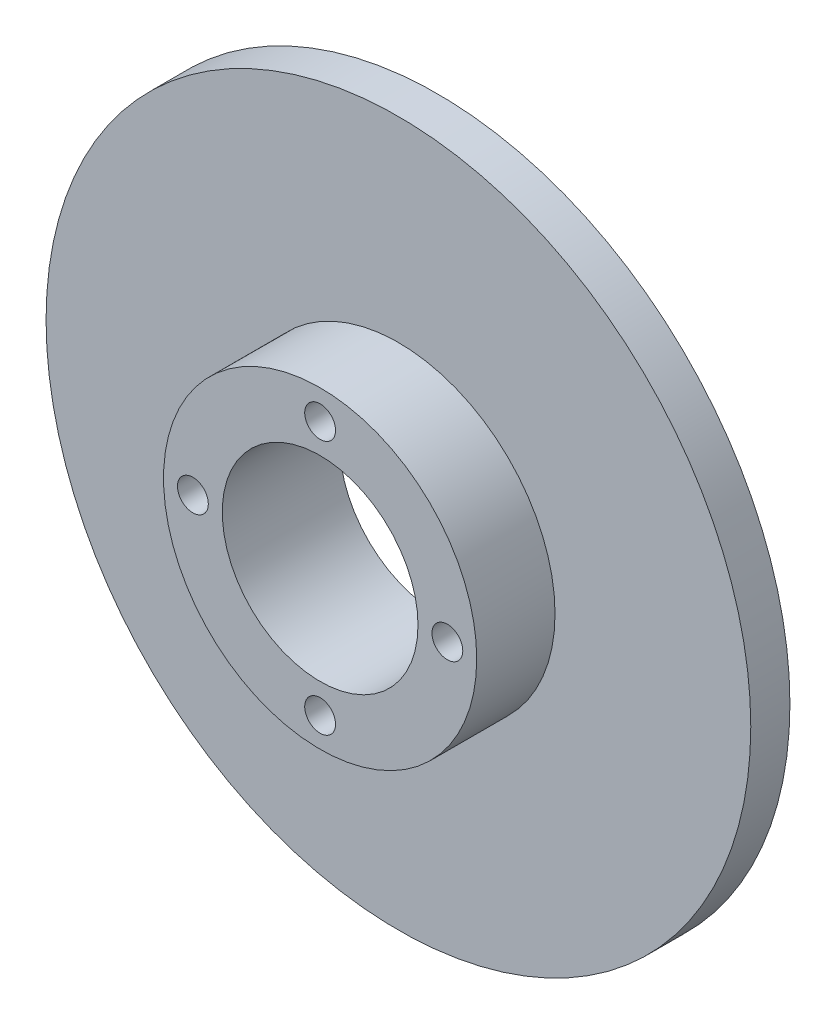
SolidWorks part; units mm, degrees
material "Stainless Steel (ferritic)"
ref_plane "Front Plane" through (0, 0, 0) normal (0, 0, 1) x (1, 0, 0)
ref_plane "Top Plane" through (0, 0, 0) normal (0, 1, 0) x (1, 0, 0)
ref_plane "Right Plane" through (0, 0, 0) normal (1, 0, 0) x (0, 0, -1)
sketch "Sketch1" plane through (0, 0, 0) normal (0, 0, 1) x (1, 0, 0)
  circle A0 centre (0, 0) radius 114.3
  dimension "D1" = 228.6
extrude "Boss-Extrude1" add sketch "Sketch1" along normal blind 12.7
sketch "Sketch2" plane through (0, 0, 12.7) normal (0, 0, 1) x (1, 0, 0)
  circle A0 centre (0, 0) radius 50.8
  dimension "D1" = 101.6
extrude "Boss-Extrude2" add sketch "Sketch2" along normal blind 25.4
sketch "Sketch3" plane through (0, 0, 38.1) normal (0, 0, 1) x (1, 0, 0)
  circle A0 centre (0, 0) radius 31.75
  circle A1 centre (0, 0) radius 50.8 construction
  dimension "D1" = 19.05
extrude "Cut-Extrude1" cut sketch "Sketch3" against normal blind 118.11
sketch "Sketch4" plane through (0, 0, 38.1) normal (0, 0, 1) x (1, 0, 0)
  line L0 (0, 0) -> (0, 114.3) construction
  circle A0 centre (0, 0) radius 114.3 construction
  circle A1 centre (0, 0) radius 41.275
  circle A2 centre (0, 0) radius 50.8 construction
  circle A3 centre (0, 41.275) radius 5
  circle A4 centre (41.275, 0) radius 5
  circle A5 centre (0, -41.275) radius 5
  circle A6 centre (-41.275, 0) radius 5
  point P20 (0, 0)
  dimension "D1" = 9.525
  dimension "D2" = 10
  dimension "D3" = 4
extrude "Cut-Extrude2" cut sketch "Sketch4" against normal blind 118.11 contours A1 A6 | A1 A6 | A1 L0 A3 | L0 A1 A3 | L0 A3 A1 | A3 L0 A1 | A1 A4 | A1 A5 | A1 A5 | A1 A4
